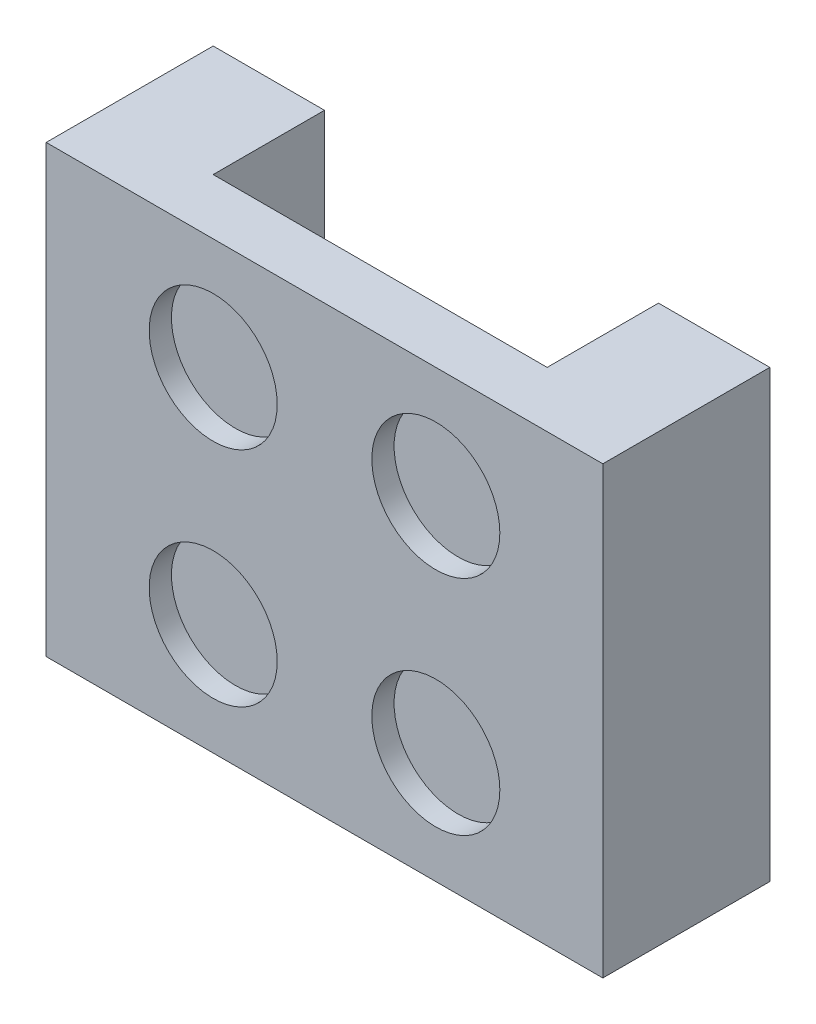
SolidWorks part; units mm, degrees
ref_plane "前视基准面" through (0, 0, 0) normal (0, 0, 1) x (1, 0, 0)
ref_plane "上视基准面" through (0, 0, 0) normal (0, 1, 0) x (1, 0, 0)
ref_plane "右视基准面" through (0, 0, 0) normal (1, 0, 0) x (0, 0, -1)
other "Configuration Table"
sketch "草图1" plane through (0, 0, 0) normal (0, 1, 0) x (1, 0, 0)
  line L3 (0, 0) -> (0, -15)
  line L4 (0, -15) -> (50, -15)
  line L5 (50, -15) -> (50, 0)
  line L6 (50, 0) -> (40, 0)
  line L7 (40, 0) -> (40, -10)
  line L8 (40, -10) -> (10, -10)
  line L9 (10, -10) -> (10, 0)
  line L10 (10, 0) -> (0, 0)
  dimension "D1" = 30
  dimension "D2" = 10
  dimension "D3" = 15
  dimension "D4" = 5
extrude "凸台-拉伸1" add sketch "草图1" along normal blind 40
sketch "草图2" plane through (0, 0, 15) normal (0, 0, 1) x (1, 0, 0)
  line L0 (0, 40) -> (0, 0) construction
  line L2 (0, 40) -> (50, 40) construction
  line L3 (50, 40) -> (50, 0) construction
  line L4 (0, 0) -> (50, 0) construction
  circle A0 centre (15, 30) radius 5.75
  circle A1 centre (35, 30) radius 5.75
  circle A2 centre (15, 10) radius 5.75
  circle A3 centre (35, 10) radius 5.75
  point P16 (0, 0)
  point P17 (0, 0)
  point P18 (0, 0)
  point P19 (0, 0)
  dimension "D1" = 11.5
  dimension "D2" = 15
  dimension "D3" = 15
  dimension "D4" = 10
  dimension "D5" = 10
extrude "切除-拉伸1" cut sketch "草图2" against normal blind 2
